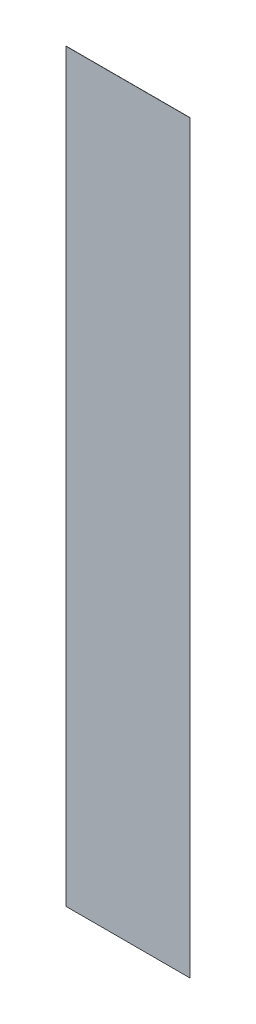
SolidWorks part; units mm, degrees
ref_plane "前视" through (0, 0, 0) normal (0, 0, 1) x (1, 0, 0)
ref_plane "上视" through (0, 0, 0) normal (0, 1, 0) x (1, 0, 0)
ref_plane "右视" through (0, 0, 0) normal (1, 0, 0) x (0, 0, -1)
sketch "草图1" plane through (0, 0, 0) normal (0, 0, 1) x (1, 0, 0)
  line L1 (-39.4126, 31.413) -> (5960.5874, 31.413)
  line L2 (-39.4126, 31.413) -> (-39.4126, -35968.587)
  line L3 (-39.4126, -35968.587) -> (5960.5874, -35968.587)
  line L4 (5960.5874, 31.413) -> (5960.5874, -35968.587)
  dimension "D1" = 6000
  dimension "D2" = 36000
extrude "拉伸1" add sketch "草图1" along normal blind 10
